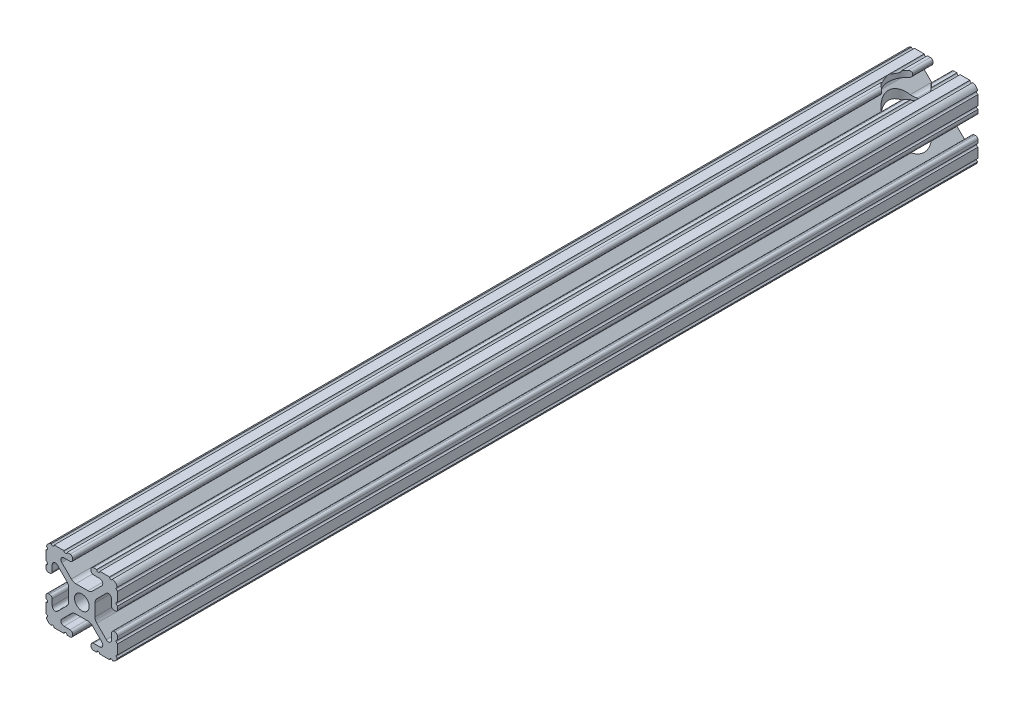
SolidWorks part; units mm, degrees
ref_plane "Front Plane" through (0, 0, 0) normal (0, 0, 1) x (1, 0, 0)
ref_plane "Top Plane" through (0, 0, 0) normal (0, 1, 0) x (1, 0, 0)
ref_plane "Right Plane" through (0, 0, 0) normal (1, 0, 0) x (0, 0, -1)
sketch "Sketch1" plane through (0, 0, 0) normal (0, 0, 1) x (1, 0, 0)
  line L0 (-3.7373, -5.2999) -> (-7.1039, -8.6665)
  line L1 (-6.3485, -10.4902) -> (-4.1904, -10.4902)
  line L2 (-3.2512, -11.4294) -> (-3.2512, -11.7608)
  line L3 (-4.1904, -12.7) -> (-5.2436, -12.7)
  line L4 (-6.3485, -12.7) -> (-9.8037, -12.7)
  line L5 (-12.7, -9.8037) -> (-12.7, -6.3485)
  line L6 (-12.7, -5.2436) -> (-12.7, -4.1904)
  line L7 (-11.7608, -3.2512) -> (-11.4294, -3.2512)
  line L8 (-10.4902, -4.1904) -> (-10.4902, -6.3485)
  line L9 (-8.6665, -7.1039) -> (-5.2999, -3.7373)
  line L10 (-4.6482, -2.164) -> (-4.6482, 2.164)
  line L11 (-8.6665, 7.1039) -> (-5.2999, 3.7373)
  line L12 (-10.4902, 4.1904) -> (-10.4902, 6.3485)
  line L13 (-11.7608, 3.2512) -> (-11.4294, 3.2512)
  line L14 (-12.7, 5.2436) -> (-12.7, 4.1904)
  line L15 (-12.7, 9.8037) -> (-12.7, 6.3485)
  line L16 (-6.3485, 12.7) -> (-9.8037, 12.7)
  line L17 (-4.1904, 12.7) -> (-5.2436, 12.7)
  line L18 (-3.2512, 11.4294) -> (-3.2512, 11.7608)
  line L19 (-6.3485, 10.4902) -> (-4.1904, 10.4902)
  line L20 (-3.7373, 5.2999) -> (-7.1039, 8.6665)
  line L21 (-2.164, 4.6482) -> (2.164, 4.6482)
  line L22 (3.7373, 5.2999) -> (7.1039, 8.6665)
  line L23 (6.3485, 10.4902) -> (4.1904, 10.4902)
  line L24 (3.2512, 11.4294) -> (3.2512, 11.7608)
  line L25 (4.1904, 12.7) -> (5.2436, 12.7)
  line L26 (6.3485, 12.7) -> (9.8037, 12.7)
  line L27 (12.7, 9.8037) -> (12.7, 6.3485)
  line L28 (12.7, 5.2436) -> (12.7, 4.1904)
  line L29 (11.7608, 3.2512) -> (11.4294, 3.2512)
  line L30 (10.4902, 4.1904) -> (10.4902, 6.3485)
  line L31 (8.6665, 7.1039) -> (5.2999, 3.7373)
  line L32 (3.2512, -11.4294) -> (3.2512, -11.7608)
  line L33 (6.3485, -10.4902) -> (4.1904, -10.4902)
  line L34 (3.7373, -5.2999) -> (7.1039, -8.6665)
  line L35 (-2.164, -4.6482) -> (2.164, -4.6482)
  line L36 (4.6482, -2.164) -> (4.6482, 2.164)
  line L37 (8.6665, -7.1039) -> (5.2999, -3.7373)
  line L38 (10.4902, -4.1904) -> (10.4902, -6.3485)
  line L39 (11.7608, -3.2512) -> (11.4294, -3.2512)
  line L40 (12.7, -5.2436) -> (12.7, -4.1904)
  line L41 (6.3485, -12.7) -> (9.8037, -12.7)
  line L42 (12.7, -9.8037) -> (12.7, -6.3485)
  line L43 (4.1904, -12.7) -> (5.2436, -12.7)
  circle A0 centre (0, 0) radius 2.6035
  arc A1 (12.7, -9.8037) -> (12.58, -10.8954) centre (12.7, -10.3562) ccw
  arc A2 (10.8954, -12.58) -> (9.8037, -12.7) centre (10.3562, -12.7) ccw
  arc A3 (6.3485, -12.7) -> (5.2436, -12.7) centre (5.796, -12.7) ccw
  arc A4 (-2.164, -4.6482) -> (-3.7373, -5.2999) centre (-2.164, -6.8732) ccw
  arc A5 (-7.1039, -8.6665) -> (-6.3485, -10.4902) centre (-6.3485, -9.4219) ccw
  arc A6 (-3.2512, -11.4294) -> (-4.1904, -10.4902) centre (-4.1904, -11.4294) ccw
  arc A7 (-4.1904, -12.7) -> (-3.2512, -11.7608) centre (-4.1904, -11.7608) ccw
  arc A8 (-5.2436, -12.7) -> (-6.3485, -12.7) centre (-5.796, -12.7) ccw
  arc A9 (-9.8037, -12.7) -> (-10.8954, -12.58) centre (-10.3562, -12.7) ccw
  arc A10 (-12.58, -10.8954) -> (-10.8954, -12.58) centre (-10.1173, -10.1173) ccw
  arc A11 (-12.58, -10.8954) -> (-12.7, -9.8037) centre (-12.7, -10.3562) ccw
  arc A12 (-12.7, -6.3485) -> (-12.7, -5.2436) centre (-12.7, -5.796) ccw
  arc A13 (-11.7608, -3.2512) -> (-12.7, -4.1904) centre (-11.7608, -4.1904) ccw
  arc A14 (-10.4902, -4.1904) -> (-11.4294, -3.2512) centre (-11.4294, -4.1904) ccw
  arc A15 (-10.4902, -6.3485) -> (-8.6665, -7.1039) centre (-9.4219, -6.3485) ccw
  arc A16 (-5.2999, -3.7373) -> (-4.6482, -2.164) centre (-6.8732, -2.164) ccw
  arc A17 (-4.6482, 2.164) -> (-5.2999, 3.7373) centre (-6.8732, 2.164) ccw
  arc A18 (-8.6665, 7.1039) -> (-10.4902, 6.3485) centre (-9.4219, 6.3485) ccw
  arc A19 (-11.4294, 3.2512) -> (-10.4902, 4.1904) centre (-11.4294, 4.1904) ccw
  arc A20 (-12.7, 4.1904) -> (-11.7608, 3.2512) centre (-11.7608, 4.1904) ccw
  arc A21 (-12.7, 5.2436) -> (-12.7, 6.3485) centre (-12.7, 5.796) ccw
  arc A22 (-12.7, 9.8037) -> (-12.58, 10.8954) centre (-12.7, 10.3562) ccw
  arc A23 (-10.8954, 12.58) -> (-12.58, 10.8954) centre (-10.1173, 10.1173) ccw
  arc A24 (-10.8954, 12.58) -> (-9.8037, 12.7) centre (-10.3562, 12.7) ccw
  arc A25 (-6.3485, 12.7) -> (-5.2436, 12.7) centre (-5.796, 12.7) ccw
  arc A26 (-3.2512, 11.7608) -> (-4.1904, 12.7) centre (-4.1904, 11.7608) ccw
  arc A27 (-4.1904, 10.4902) -> (-3.2512, 11.4294) centre (-4.1904, 11.4294) ccw
  arc A28 (-6.3485, 10.4902) -> (-7.1039, 8.6665) centre (-6.3485, 9.4219) ccw
  arc A29 (-3.7373, 5.2999) -> (-2.164, 4.6482) centre (-2.164, 6.8732) ccw
  arc A30 (2.164, 4.6482) -> (3.7373, 5.2999) centre (2.164, 6.8732) ccw
  arc A31 (7.1039, 8.6665) -> (6.3485, 10.4902) centre (6.3485, 9.4219) ccw
  arc A32 (3.2512, 11.4294) -> (4.1904, 10.4902) centre (4.1904, 11.4294) ccw
  arc A33 (4.1904, 12.7) -> (3.2512, 11.7608) centre (4.1904, 11.7608) ccw
  arc A34 (5.2436, 12.7) -> (6.3485, 12.7) centre (5.796, 12.7) ccw
  arc A35 (9.8037, 12.7) -> (10.8954, 12.58) centre (10.3562, 12.7) ccw
  arc A36 (12.58, 10.8954) -> (10.8954, 12.58) centre (10.1173, 10.1173) ccw
  arc A37 (12.58, 10.8954) -> (12.7, 9.8037) centre (12.7, 10.3562) ccw
  arc A38 (12.7, 6.3485) -> (12.7, 5.2436) centre (12.7, 5.796) ccw
  arc A39 (11.7608, 3.2512) -> (12.7, 4.1904) centre (11.7608, 4.1904) ccw
  arc A40 (10.4902, 4.1904) -> (11.4294, 3.2512) centre (11.4294, 4.1904) ccw
  arc A41 (10.4902, 6.3485) -> (8.6665, 7.1039) centre (9.4219, 6.3485) ccw
  arc A42 (5.2999, 3.7373) -> (4.6482, 2.164) centre (6.8732, 2.164) ccw
  arc A43 (12.7, -5.2436) -> (12.7, -6.3485) centre (12.7, -5.796) ccw
  arc A44 (4.1904, -10.4902) -> (3.2512, -11.4294) centre (4.1904, -11.4294) ccw
  arc A45 (6.3485, -10.4902) -> (7.1039, -8.6665) centre (6.3485, -9.4219) ccw
  arc A46 (3.7373, -5.2999) -> (2.164, -4.6482) centre (2.164, -6.8732) ccw
  arc A47 (4.6482, -2.164) -> (5.2999, -3.7373) centre (6.8732, -2.164) ccw
  arc A48 (8.6665, -7.1039) -> (10.4902, -6.3485) centre (9.4219, -6.3485) ccw
  arc A49 (11.4294, -3.2512) -> (10.4902, -4.1904) centre (11.4294, -4.1904) ccw
  arc A50 (12.7, -4.1904) -> (11.7608, -3.2512) centre (11.7608, -4.1904) ccw
  arc A51 (10.8954, -12.58) -> (12.58, -10.8954) centre (10.1173, -10.1173) ccw
  arc A52 (3.2512, -11.7608) -> (4.1904, -12.7) centre (4.1904, -11.7608) ccw
extrude "Boss-Extrude1" add sketch "Sketch1" along normal blind 304.8
sketch "Sketch3" plane through (0, 12.7, 0) normal (0, 1, 0) x (1, 0, 0)
  line L0 (12.7, -304.8) -> (12.7, 0) construction
  line L5 (-12.7, 0) -> (12.7, -25.4) construction
  circle A0 centre (0, -12.7) radius 6.35
  dimension "D2" = 12.7
  dimension "D1" = 25.4
extrude "Cut-Extrude1" cut sketch "Sketch3" against normal through all
